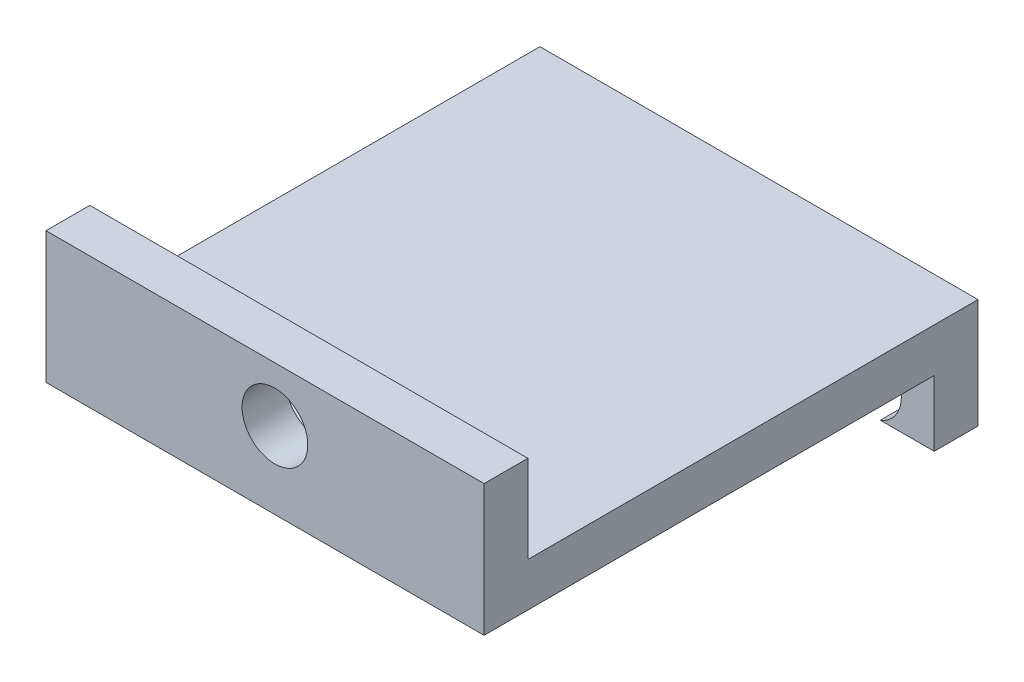
SolidWorks part; units mm, degrees
ref_plane "Front" through (0, 0, 0) normal (0, 0, 1) x (1, 0, 0)
ref_plane "Top" through (0, 0, 0) normal (0, 1, 0) x (1, 0, 0)
ref_plane "Right" through (0, 0, 0) normal (1, 0, 0) x (0, 0, -1)
sketch "Esquisse1" plane through (0, 0, 0) normal (0, 0, 1) x (1, 0, 0)
  line L1 (-10, -2.5) -> (10, -2.5)
  line L2 (-10, -2.5) -> (-10, 2.5)
  line L3 (-10, 2.5) -> (10, 2.5)
  line L4 (10, -2.5) -> (10, 2.5)
  line L5 (-10, -2.5) -> (10, 2.5) construction
  line L6 (-10, 2.5) -> (10, -2.5) construction
  circle A0 centre (-7, -1.1) radius 1.5
  circle A1 centre (7, -1.1) radius 1.5
  point P0 (0, 0)
  point P10 (0, 0)
  dimension "D3" = 3
  dimension "D4" = 3
  dimension "D1" = 5
  dimension "D2" = 20
  dimension "D5" = 3
  dimension "D6" = 3
  dimension "D7" = 3.6
  dimension "D8" = 3.6
extrude "Boss.-Extru.2" add sketch "Esquisse1" along normal blind 2 contours A1 L1 L4 L3 L2 A0
sketch "Esquisse2" plane through (0, 0, 2) normal (0, 0, 1) x (1, 0, 0)
  line L0 (10, -2.5) -> (10, 2.5) construction
  line L1 (-10, 2.5) -> (10, 2.5)
  line L2 (-10, 2.5) -> (-10, 0.5)
  line L3 (-10, 0.5) -> (10, 0.5)
  line L4 (10, 2.5) -> (10, 0.5)
  dimension "D1" = 2
extrude "Boss.-Extru.3" add sketch "Esquisse2" along normal blind 20.55
sketch "Esquisse3" plane through (0, 2.5, 0) normal (0, 1, 0) x (1, 0, 0)
  line L0 (10, -22.55) -> (10, 0) construction
  line L1 (-10, -22.55) -> (10, -22.55)
  line L2 (-10, -22.55) -> (-10, -20.55)
  line L3 (-10, -20.55) -> (10, -20.55)
  line L4 (10, -22.55) -> (10, -20.55)
  dimension "D1" = 2
extrude "Boss.-Extru.4" add sketch "Esquisse3" along normal blind 4
sketch "Esquisse4" plane through (0, 0, 22.55) normal (0, 0, 1) x (1, 0, 0)
  line L0 (-10, 6.5) -> (10, 6.5) construction
  line L2 (10, 0.5) -> (10, 6.5) construction
  circle A0 centre (0.45, 4) radius 1.5
  dimension "D1" = 3
  dimension "D2" = 2.5
  dimension "D3" = 9.55
extrude "Enlèv. mat.-Extru.1" cut sketch "Esquisse4" against normal blind 4
